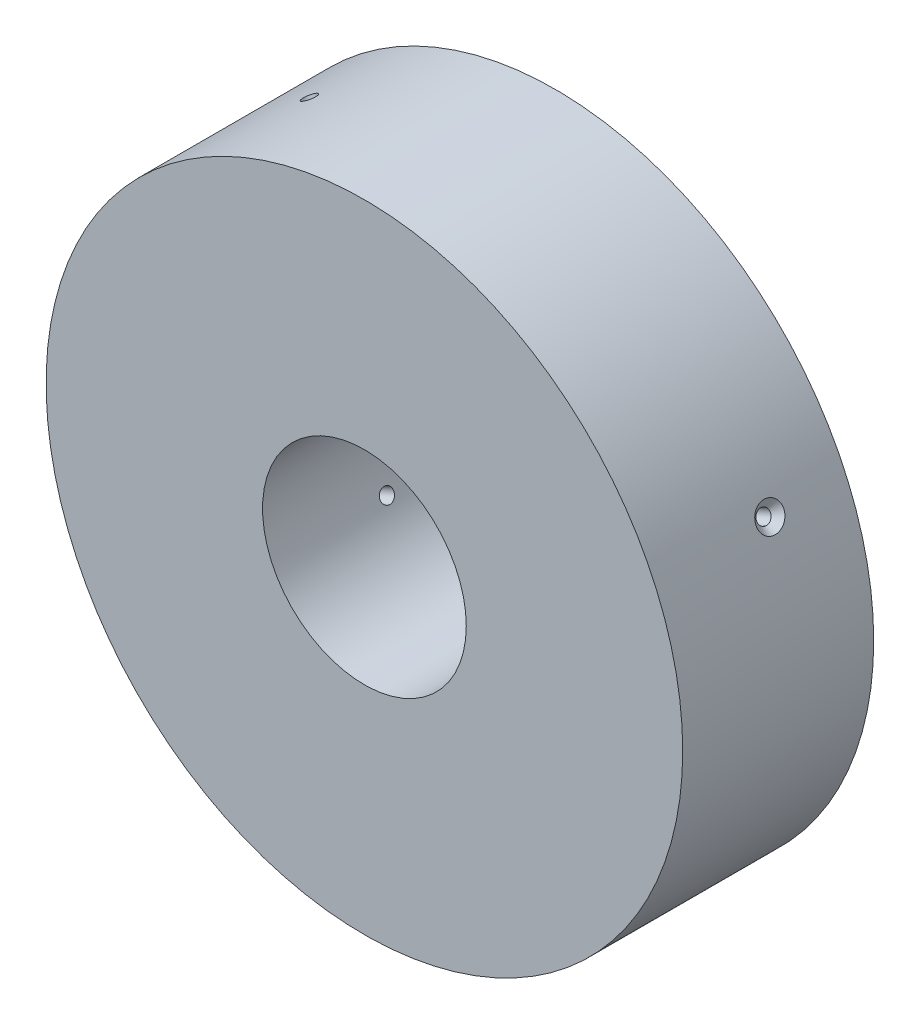
SolidWorks part; units mm, degrees
ref_plane "Front Plane" through (0, 0, 0) normal (0, 0, 1) x (1, 0, 0)
ref_plane "Top Plane" through (0, 0, 0) normal (0, 1, 0) x (1, 0, 0)
ref_plane "Right Plane" through (0, 0, 0) normal (1, 0, 0) x (0, 0, -1)
sketch "Sketch2" plane through (0, 0, 0) normal (0, 0, 1) x (1, 0, 0)
  circle A0 centre (0, 0) radius 50
  circle A1 centre (0, 0) radius 16
extrude "Boss-Extrude1" add sketch "Sketch2" along normal blind 30
hole_wizard "CSK for M2 Countersunk Flat Head Screw1" positions "3DSketch4" profile "Sketch10" countersink size "M2" standard "DIN" end condition through all
sketch3d "3DSketch4"
  point P0 (24.8735, -43.3741, 13.7715)
  point P2 (45.5767, 20.5612, 11.8892)
sketch "Sketch10" plane through (24.8735, -43.3741, 13.7715) normal (0, 0, 1) x (0.8675, 0.4975, 0)
  line L0 (0, 0) -> (0, 118.2476)
  line L1 (0, 118.2476) -> (1.1, 118.2476)
  line L2 (1.1, 118.2476) -> (1.1, 1.1)
  line L3 (1.1, 1.1) -> (2.2, 0)
  line L5 (2.2, 0) -> (0, 0)
  line L6 (-1.1, 1.1) -> (-2.2, 0) construction
  line L11 (0, -6.35) -> (0, 107.95) construction
  dimension "Thru Hole Dia." = 2.2
  dimension "Thru Hole Depth" = 118.2476
  dimension "Near C'Sink Dia." = 4.4
  dimension "Near C'Sink Angle" = 90
